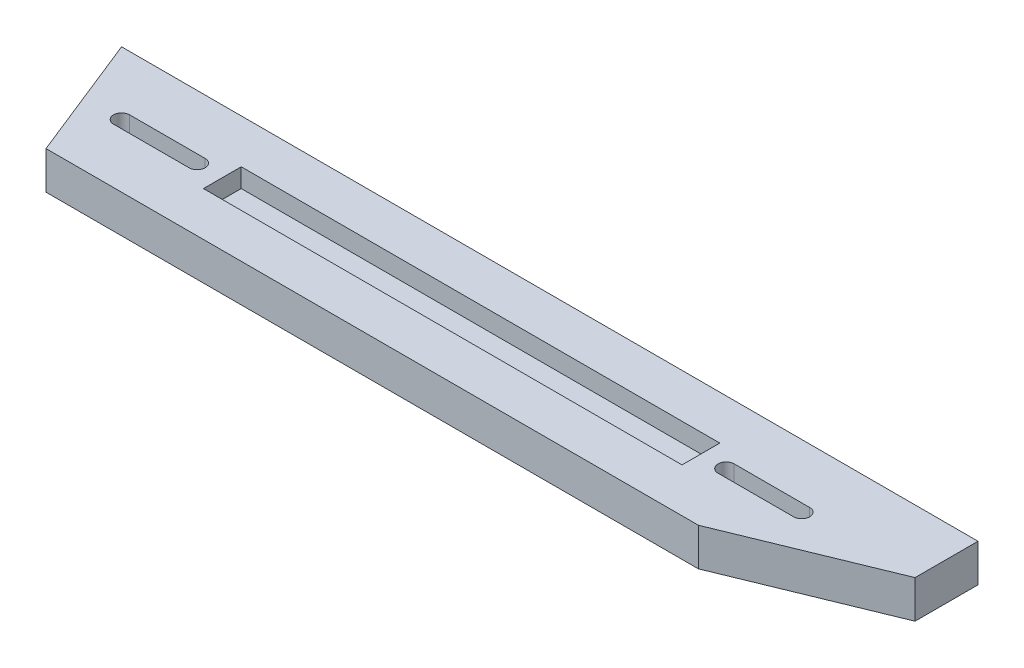
SolidWorks part; units mm, degrees
ref_plane "Front" through (0, 0, 0) normal (0, 0, 1) x (1, 0, 0)
ref_plane "Top" through (0, 0, 0) normal (0, 1, 0) x (1, 0, 0)
ref_plane "Right" through (0, 0, 0) normal (1, 0, 0) x (0, 0, -1)
sketch "Sketch1" plane through (0, 0, 0) normal (0, 1, 0) x (1, 0, 0)
  line L1 (215.9, -31.75) -> (-215.9, -31.75)
  line L2 (215.9, -31.75) -> (215.9, 31.75)
  line L3 (215.9, 31.75) -> (-215.9, 31.75)
  line L4 (-215.9, -31.75) -> (-215.9, 31.75)
  line L5 (215.9, -31.75) -> (-215.9, 31.75) construction
  line L6 (215.9, 31.75) -> (-215.9, -31.75) construction
  point P0 (0, 0)
  dimension "D1" = 63.5
  dimension "D2" = 431.8
extrude "Boss-Extrude1" add sketch "Sketch1" along normal blind 19.05
sketch "Sketch3" plane through (0, 19.05, 0) normal (0, 1, 0) x (1, 0, 0)
  line L0 (-215.9, 31.75) -> (-190.5, -31.75)
  line L1 (-215.9, -31.75) -> (215.9, -31.75) construction
  line L2 (-190.5, -31.75) -> (-215.9, -31.75)
  line L3 (-215.9, 31.75) -> (-215.9, -31.75) construction
  line L4 (-215.9, -31.75) -> (-215.9, 31.75)
  line L5 (0, 0) -> (0, -31.75) construction
  line L6 (215.9, 0) -> (138.43, -31.75)
  line L7 (215.9, -31.75) -> (215.9, 31.75) construction
  line L8 (138.43, -31.75) -> (215.9, -31.75)
  line L9 (215.9, -31.75) -> (215.9, 0)
  dimension "D1" = 25.4
  dimension "D2" = 31.75
  dimension "D3" = 77.47
extrude "Cut-Extrude2" cut sketch "Sketch3" against normal through all
sketch "Sketch2" plane through (0, 19.05, 0) normal (0, 1, 0) x (1, 0, 0)
  line L0 (158.75, 0) -> (120.65, 0) construction
  line L1 (158.75, -4.064) -> (120.65, -4.064)
  line L2 (158.75, 4.064) -> (120.65, 4.064)
  line L4 (0, 0) -> (-165.1, 0) construction
  line L6 (-184.15, 0) -> (-146.05, 0) construction
  line L7 (-184.15, 4.064) -> (-146.05, 4.064)
  line L8 (-184.15, -4.064) -> (-146.05, -4.064)
  line L10 (0, 0) -> (139.7, 0) construction
  line L11 (215.9, 0) -> (215.9, 31.75) construction
  arc A0 (158.75, -4.064) -> (158.75, 4.064) centre (158.75, 0) ccw
  arc A1 (120.65, 4.064) -> (120.65, -4.064) centre (120.65, 0) ccw
  arc A2 (-184.15, 4.064) -> (-184.15, -4.064) centre (-184.15, 0) ccw
  arc A3 (-146.05, -4.064) -> (-146.05, 4.064) centre (-146.05, 0) ccw
  point P2 (139.7, 0)
  point P17 (-165.1, 0)
  dimension "D4" = 8.128
  dimension "D1" = 8.128
  dimension "D2" = 38.1
  dimension "D3" = 31.75
  dimension "D5" = 57.15
  dimension "D6" = 38.1
extrude "Cut-Extrude1" cut sketch "Sketch2" against normal blind 19.05
sketch "Sketch4" plane through (0, 19.05, 0) normal (0, 1, 0) x (1, 0, 0)
  line L0 (0, 0) -> (184.15, 0) construction
  circle A0 centre (184.15, 0) radius 4.064
  arc A1 (-184.15, 4.064) -> (-184.15, -4.064) centre (-184.15, 0) ccw construction
  dimension "D1" = 8.128
  dimension "D2" = 368.3
extrude "Boss-Extrude2" [suppressed] add sketch "Sketch4" along normal blind 25.4
sketch "Sketch5" plane through (0, 19.05, 0) normal (0, 1, 0) x (1, 0, 0)
  line L0 (-37.4893, 31.75) -> (-37.4893, 9.525) construction
  line L1 (-133.35, 9.525) -> (107.95, 9.525)
  line L2 (-133.35, 9.525) -> (-133.35, -9.525)
  line L3 (-133.35, -9.525) -> (107.95, -9.525)
  line L4 (107.95, 9.525) -> (107.95, -9.525)
  line L5 (215.9, 31.75) -> (-215.9, 31.75) construction
  line L6 (-37.4893, 9.525) -> (-37.4893, -9.525) construction
  line L7 (-37.4893, -9.525) -> (-37.4893, -31.75) construction
  line L8 (-190.5, -31.75) -> (138.43, -31.75) construction
  arc A0 (-146.05, -4.064) -> (-146.05, 4.064) centre (-146.05, 0) ccw construction
  dimension "D1" = 19.05
  dimension "D2" = 241.3
  dimension "D3" = 12.7
extrude "Cut-Extrude3" cut sketch "Sketch5" against normal blind 9.525
